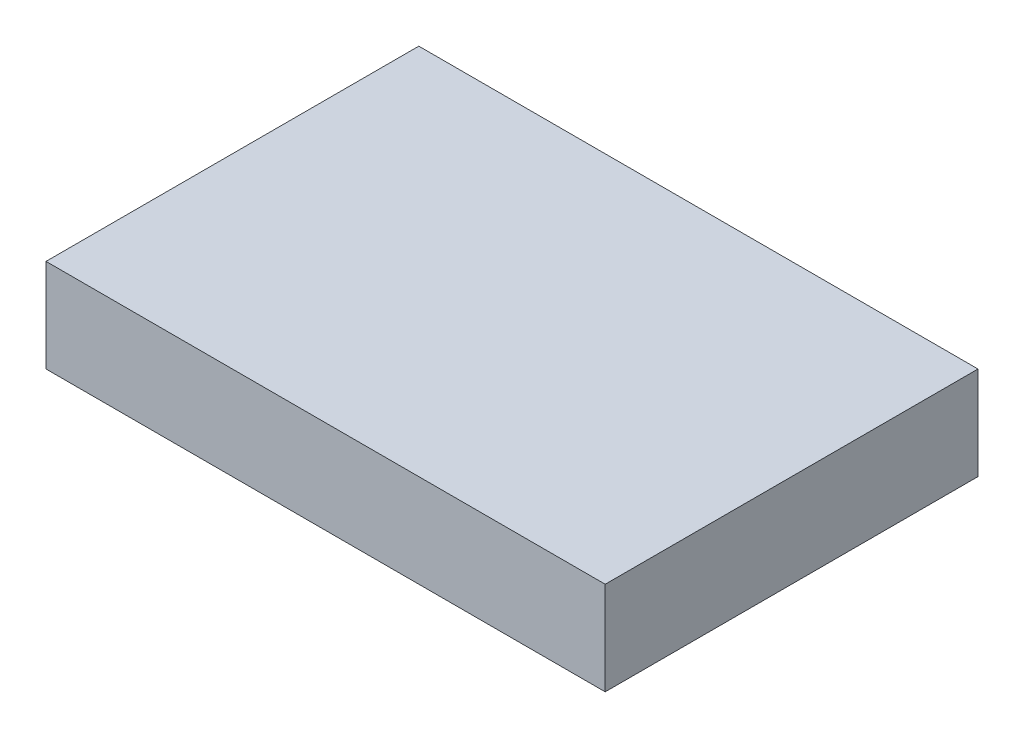
SolidWorks part; units mm, degrees
ref_plane "Front Plane" through (0, 0, 0) normal (0, 0, 1) x (1, 0, 0)
ref_plane "Top Plane" through (0, 0, 0) normal (0, 1, 0) x (1, 0, 0)
ref_plane "Right Plane" through (0, 0, 0) normal (1, 0, 0) x (0, 0, -1)
sketch "Sketch1" plane through (0, 0, 0) normal (0, 1, 0) x (1, 0, 0)
  line L0 (-1.9226, -3.3301) -> (1.9226, -3.3301)
  line L1 (2.5, -4.3301) -> (5, 0)
  line L2 (5, 0) -> (2.5, 4.3301)
  line L3 (2.5, 4.3301) -> (-2.5, 4.3301)
  line L4 (-2.5, 4.3301) -> (-5, 0)
  line L5 (-5, 0) -> (-2.5, -4.3301)
  line L6 (-2.5, -4.3301) -> (2.5, -4.3301)
  line L7 (10, -8.6603) -> (12.5, -4.3301)
  line L8 (12.5, -4.3301) -> (10, 0)
  line L9 (10, 0) -> (5, 0)
  line L10 (5, 0) -> (2.5, -4.3301)
  line L11 (2.5, -4.3301) -> (5, -8.6603)
  line L12 (5, -8.6603) -> (10, -8.6603)
  line L13 (1.9226, -3.3301) -> (3.8453, 0)
  line L14 (3.8453, 0) -> (1.9226, 3.3301)
  line L15 (1.9226, 3.3301) -> (-1.9226, 3.3301)
  line L16 (-1.9226, 3.3301) -> (-3.8453, 0)
  line L17 (-3.8453, 0) -> (-1.9226, -3.3301)
  line L18 (9.4226, -7.6603) -> (11.3453, -4.3301)
  line L19 (11.3453, -4.3301) -> (9.4226, -1)
  line L20 (9.4226, -1) -> (5.5774, -1)
  line L21 (5.5774, -1) -> (3.6547, -4.3301)
  line L22 (3.6547, -4.3301) -> (5.5774, -7.6603)
  line L23 (5.5774, -7.6603) -> (9.4226, -7.6603)
  line L24 (-8.7975, 0) -> (22.1646, 0) construction
  line L25 (0, 8.3315) -> (0, -12.3148) construction
  circle A0 centre (0, 0) radius 4.3301 construction
  circle A1 centre (7.5, -4.3301) radius 4.3301 construction
  dimension "D1" = 10
  dimension "D2" = 1
  dimension "D3" = 1
sketch "Sketch2" plane through (0, 0, 0) normal (0, 1, 0) x (1, 0, 0)
  line L1 (-150, 100) -> (150, 100)
  line L2 (-150, 100) -> (-150, -100)
  line L3 (-150, -100) -> (150, -100)
  line L4 (150, 100) -> (150, -100)
  line L5 (-150, 100) -> (150, -100) construction
  line L6 (-150, -100) -> (150, 100) construction
  point P0 (0, 0)
  dimension "D1" = 300
  dimension "D2" = 200
extrude "Boss-Extrude1" add sketch "Sketch2" along normal blind 50 contours L2 L3 L4 L1
sketch "Sketch3" plane through (0, 0, 0) normal (0, -1, 0) x (-1, 0, 0)
  line L1 (150, -100) -> (-20.3038, -100)
  line L2 (150, -100) -> (150, -10.1821)
  line L3 (150, -10.1821) -> (-20.3038, -10.1821)
  line L4 (-20.3038, -100) -> (-20.3038, -10.1821)
